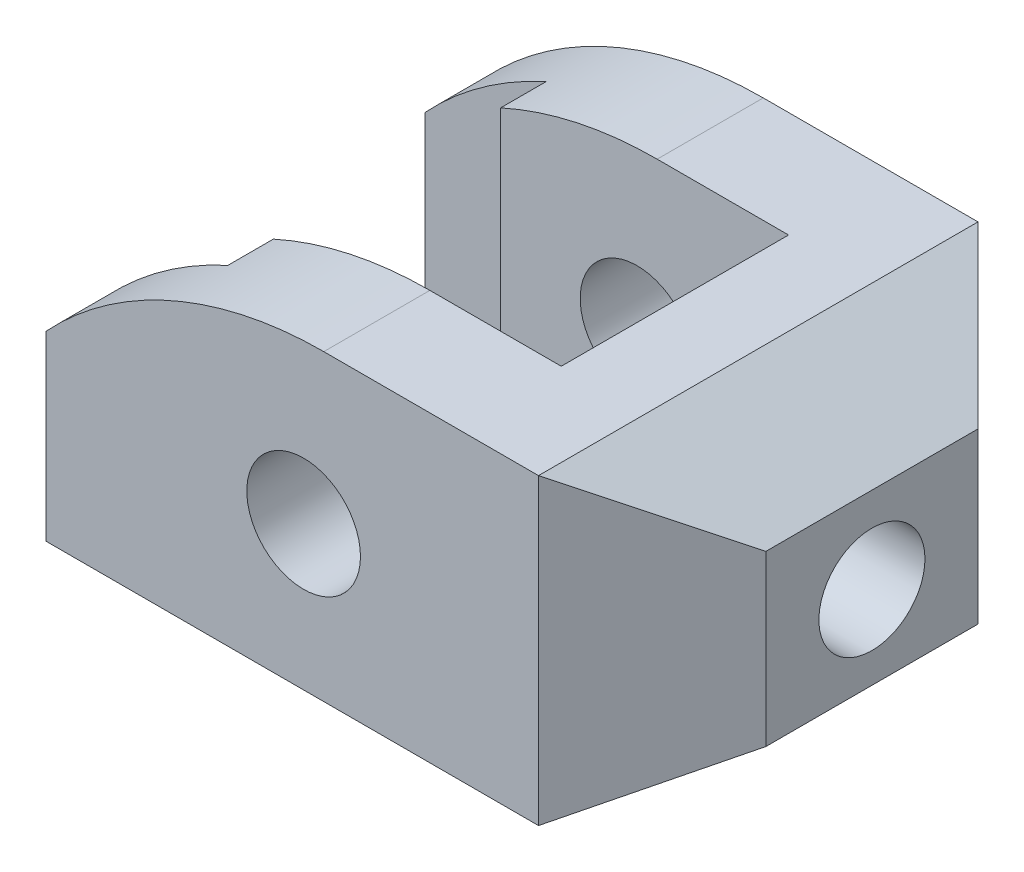
SolidWorks part; units mm, degrees
material "1060 Alloy"
ref_plane "Front Plane" through (0, 0, 0) normal (0, 0, 1) x (1, 0, 0)
ref_plane "Top Plane" through (0, 0, 0) normal (0, 1, 0) x (1, 0, 0)
ref_plane "Right Plane" through (0, 0, 0) normal (1, 0, 0) x (0, 0, -1)
sketch "Sketch2" plane through (0, 0, 0) normal (0, 0, 1) x (1, 0, 0)
  line L0 (0, 0) -> (65, 0)
  line L1 (65, 0) -> (80, 9.0293)
  line L2 (80, 9.0293) -> (80, 31.3397)
  line L3 (80, 31.3397) -> (65, 40)
  line L4 (65, 40) -> (36.6606, 40)
  line L5 (0, 0) -> (0, 24)
  arc A0 (0, 24) -> (36.6606, 40) centre (36.6606, -10) cw
  dimension "D5" = 50
  dimension "D1" = 65
  dimension "D2" = 40
  dimension "D3" = 30
  dimension "D4" = 31.046
  dimension "D6" = 24
  dimension "D7" = 15
  dimension "D8" = 15
extrude "Boss-Extrude1" add sketch "Sketch2" against normal blind 58
sketch "Sketch3" plane through (0, 0, 0) normal (0, 0, 1) x (1, 0, 0)
  line L0 (0, 0) -> (65, 0) construction
  circle A0 centre (34, 19) radius 7.5
  dimension "D3" = 15
  dimension "D1" = 19
  dimension "D2" = 31
extrude "Cut-Extrude1" cut sketch "Sketch3" against normal through all
sketch "Sketch4" plane through (0, 0, 0) normal (0, 1, 0) x (1, 0, 0)
  line L0 (65, 58) -> (80, 43)
  line L1 (80, 58) -> (80, 0) construction
  line L2 (80, 29) -> (65, 29) construction
  line L3 (65, 58) -> (65, 0) construction
  line L4 (65, 58) -> (80, 58)
  line L5 (80, 58) -> (80, 43)
  line L6 (65, 58) -> (36.6606, 58) construction
  line L7 (80, 0) -> (80, 15)
  line L8 (65, 0) -> (80, 15)
  line L9 (65, 0) -> (80, 0)
  dimension "D1" = 45
extrude "Cut-Extrude2" cut sketch "Sketch4" along normal through all
sketch "Sketch5" plane through (0, 0, 0) normal (0, -1, 0) x (1, 0, 0)
  line L0 (0, -8) -> (0, -50)
  line L1 (0, -58) -> (0, 0) construction
  line L2 (0, -8) -> (16, -8)
  line L3 (16, -8) -> (16, -14)
  line L4 (16, -14) -> (54, -14)
  line L5 (54, -14) -> (54, -44)
  line L6 (65, -29) -> (0, -29) construction
  line L7 (65, -58) -> (65, 0) construction
  line L8 (0, 0) -> (65, 0) construction
  line L9 (16, -50) -> (16, -44)
  line L10 (16, -44) -> (54, -44)
  line L11 (0, -50) -> (16, -50)
  point P14 (54, -27.9921)
  point P15 (54, -29)
  point P17 (54, -29)
  dimension "D1" = 8
  dimension "D2" = 6
  dimension "D3" = 16
  dimension "D4" = 11
extrude "Cut-Extrude3" cut sketch "Sketch5" against normal through all
sketch "Sketch6" plane through (80, 0, 0) normal (1, 0, 0) x (0, 0, -1)
  line L0 (58, 0) -> (0, 0) construction
  line L1 (0, 40) -> (0, 0) construction
  circle A0 centre (29, 20) radius 7
  dimension "D3" = 14
  dimension "D1" = 20
  dimension "D2" = 29
extrude "Cut-Extrude4" cut sketch "Sketch6" against normal through all
equation "\"A\"= 58"
equation "\"B\"= 40"
equation "\"C\"= 65"
